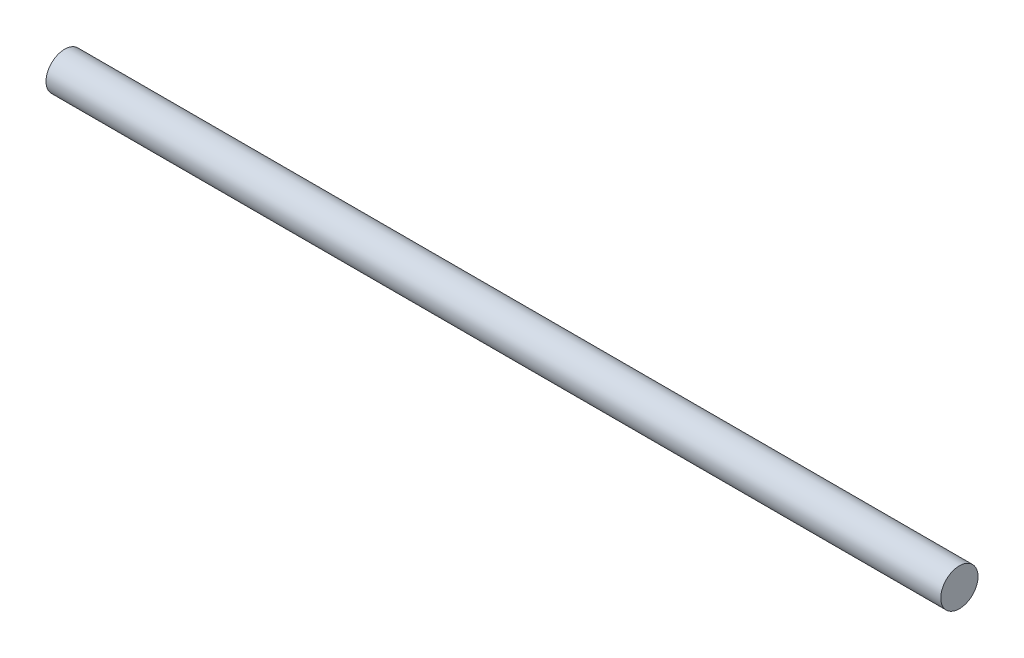
SolidWorks part; units mm, degrees
ref_plane "Front Plane" through (0, 0, 0) normal (0, 0, 1) x (1, 0, 0)
ref_plane "Top Plane" through (0, 0, 0) normal (0, 1, 0) x (1, 0, 0)
ref_plane "Right Plane" through (0, 0, 0) normal (1, 0, 0) x (0, 0, -1)
sketch "Sketch1" plane through (0, 0, 0) normal (1, 0, 0) x (0, 0, -1)
  circle A0 centre (0, 0) radius 3.175
extrude "Boss-Extrude1" add sketch "Sketch1" along normal blind 152.4
